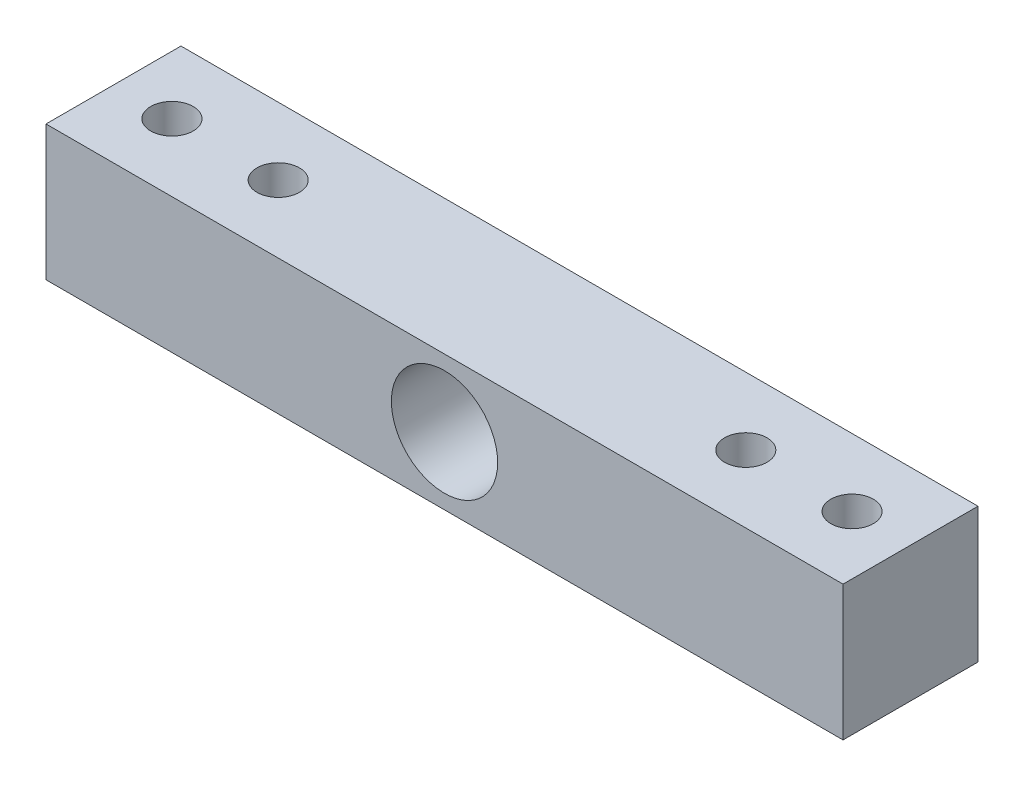
SolidWorks part; units mm, degrees
ref_plane "Front Plane" through (0, 0, 0) normal (0, 0, 1) x (1, 0, 0)
ref_plane "Top Plane" through (0, 0, 0) normal (0, 1, 0) x (1, 0, 0)
ref_plane "Right Plane" through (0, 0, 0) normal (1, 0, 0) x (0, 0, -1)
sketch "Sketch1" plane through (0, 0, 0) normal (0, 1, 0) x (1, 0, 0)
  line L1 (58.7401, 98.821) -> (133.7401, 98.821)
  line L2 (58.7401, 98.821) -> (58.7401, 111.521)
  line L3 (58.7401, 111.521) -> (133.7401, 111.521)
  line L4 (133.7401, 98.821) -> (133.7401, 111.521)
  dimension "D1" = 75
  dimension "D2" = 12.7
extrude "Boss-Extrude2" add sketch "Sketch1" along normal blind 12.7 contours L2 L3 L4 L1
sketch "Sketch2" plane through (0, 12.7, 0) normal (0, 1, 0) x (1, 0, 0)
  line L0 (58.7401, 111.521) -> (133.7401, 111.521) construction
  line L1 (58.7401, 98.821) -> (58.7401, 111.521) construction
  circle A0 centre (74.2401, 105.171) radius 2
  circle A1 centre (64.2401, 105.171) radius 2
  circle A2 centre (118.2401, 105.171) radius 2
  circle A3 centre (128.2401, 105.171) radius 2
  point P4 (96.2401, 111.521)
  point P7 (58.7401, 105.171)
  dimension "D1" = 22
  dimension "D2" = 0
  dimension "D3" = 32
  dimension "D5" = 44
  dimension "D4" = 0
  dimension "D6" = 64
  dimension "D7" = 0
  dimension "D8" = 0
extrude "Cut-Extrude1" cut sketch "Sketch2" against normal through all
sketch "Sketch3" plane through (0, 0, -98.821) normal (0, 0, 1) x (1, 0, 0)
  line L2 (58.7401, 12.7) -> (58.7401, 0) construction
  circle A0 centre (96.2401, 6.35) radius 5
  point P7 (58.7401, 6.5965)
  point P8 (58.7401, 6.35)
  dimension "D1" = 0
extrude "Cut-Extrude2" cut sketch "Sketch3" against normal through all
